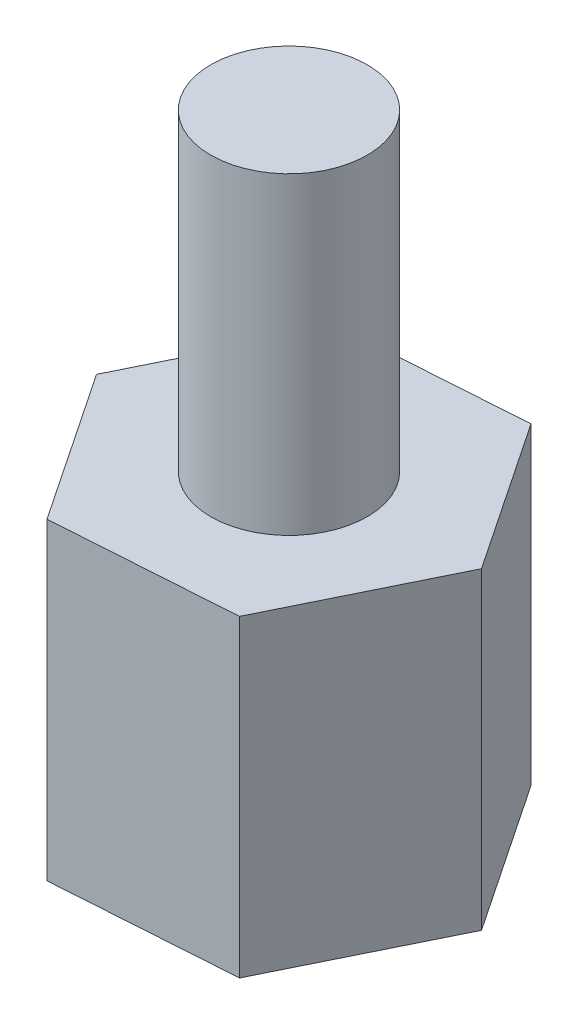
SolidWorks part; units mm, degrees
ref_plane "Front Plane" through (0, 0, 0) normal (0, 0, 1) x (1, 0, 0)
ref_plane "Top Plane" through (0, 0, 0) normal (0, 1, 0) x (1, 0, 0)
ref_plane "Right Plane" through (0, 0, 0) normal (1, 0, 0) x (0, 0, -1)
sketch "Sketch1" plane through (0, 0, 0) normal (0, 1, 0) x (1, 0, 0)
  line L1 (1.6164, 3.2906) -> (-2.0415, 3.0452)
  line L2 (-2.0415, 3.0452) -> (-3.658, -0.2454)
  line L3 (-3.658, -0.2454) -> (-1.6164, -3.2906)
  line L4 (-1.6164, -3.2906) -> (2.0415, -3.0452)
  line L5 (2.0415, -3.0452) -> (3.658, 0.2454)
  line L6 (3.658, 0.2454) -> (1.6164, 3.2906)
  circle A0 centre (0, 0) radius 3.175 construction
  dimension "D1" = 6.35
extrude "Boss-Extrude1" add sketch "Sketch1" along normal blind 6.35
sketch "Sketch2" plane through (0, 6.35, 0) normal (0, 1, 0) x (1, 0, 0)
  circle A0 centre (0, 0) radius 1.5875
  dimension "D1" = 3.175
extrude "Boss-Extrude2" add sketch "Sketch2" along normal blind 6.35
sketch "Sketch3" plane through (0, 0, 0) normal (0, -1, 0) x (-1, 0, 0)
  circle A0 centre (0, 0) radius 1.5875
extrude "Cut-Extrude1" cut sketch "Sketch3" against normal blind 4.7625
